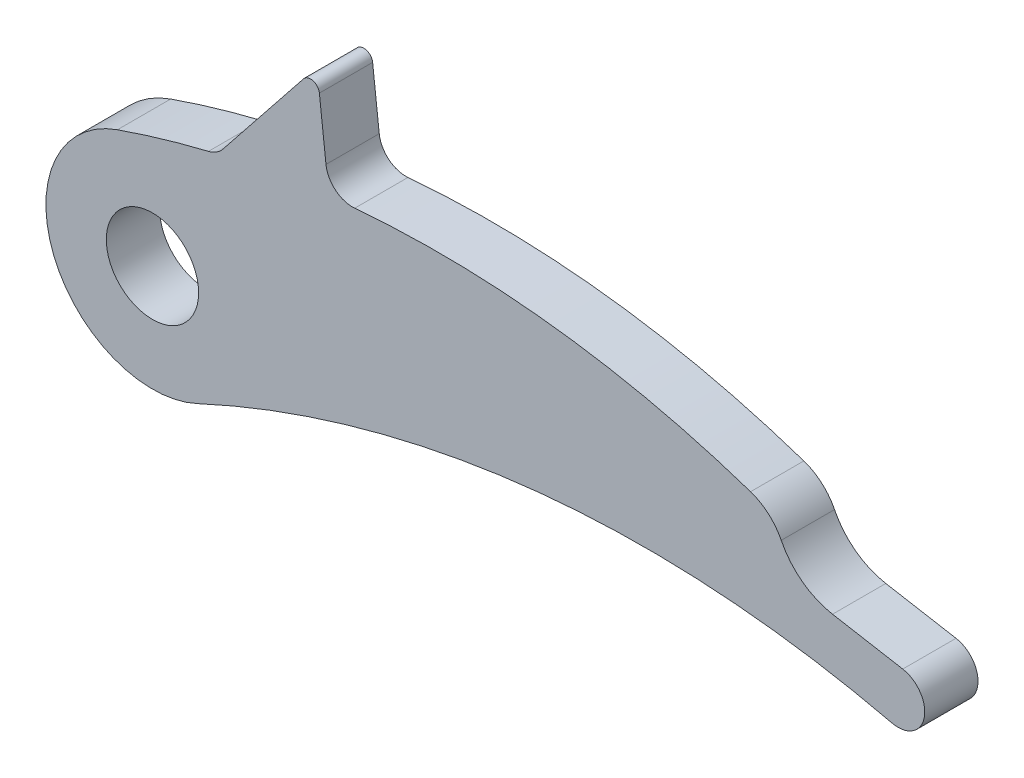
SolidWorks part; units mm, degrees
ref_plane "Plan1" through (0, 0, 0) normal (0, 0, 1) x (1, 0, 0)
ref_plane "Plan2" through (0, 0, 0) normal (0, 1, 0) x (1, 0, 0)
ref_plane "Plan3" through (0, 0, 0) normal (1, 0, 0) x (0, 0, -1)
sketch "Esquisse1" plane through (0, 0, 0) normal (0, 0, 1) x (1, 0, 0)
  line L0 (42.2605, 1.4772) -> (38.3054, 2.1746)
  line L1 (3.9745, 7.6999) -> (8.5142, 13.3962)
  line L2 (9.402, 13.1407) -> (9.774, 9.8489)
  line L3 (0, 0) -> (44.9043, 0) construction
  line L4 (9.9402, 8.3781) -> (26.3635, 10.2339) construction
  arc A0 (-1.9733, 5.6662) -> (2.53, -5.4405) centre (0, 0) ccw
  arc A1 (41.6544, -1.4596) -> (42.2605, 1.4772) centre (42, 0) ccw
  arc A2 (2.53, -5.4405) -> (41.6544, -1.4596) centre (27.8304, -59.8454) cw
  arc A3 (-1.9733, 5.6662) -> (3.1549, 7.1771) centre (16.1155, -46.2741) cw
  arc A4 (38.3054, 2.1746) -> (35.4175, 4.3345) centre (39, 6.1138) cw
  arc A5 (35.4175, 4.3345) -> (33.6893, 5.8427) centre (32.7307, 3) ccw
  arc A6 (11.3933, 8.5228) -> (33.6893, 5.8427) centre (16.1155, -46.2741) cw
  arc A7 (9.402, 13.1407) -> (8.5142, 13.3962) centre (8.9052, 13.0846) ccw
  arc A8 (11.3933, 8.5228) -> (9.774, 9.8489) centre (11.2645, 10.0173) cw
  arc A9 (3.9745, 7.6999) -> (3.1549, 7.1771) centre (2.8015, 8.6348) cw
  circle A10 centre (0, 0) radius 2.6
  point P21 (9.2665, 14.3402)
  dimension "D1" = 12
  dimension "D2" = 3
  dimension "D4" = 60
  dimension "D5" = 10
  dimension "D7" = 3
  dimension "D8" = 4
  dimension "D9" = 55
  dimension "D14" = 0.5
  dimension "D15" = 1.5
  dimension "D16" = 5.2
  dimension "D3" = 42
  dimension "D6" = 3
  dimension "D10" = 3
  dimension "D11" = 45
  dimension "D12" = 13
  dimension "D13" = 6
extrude "Base-Extrusion" add sketch "Esquisse1" along normal blind 3
